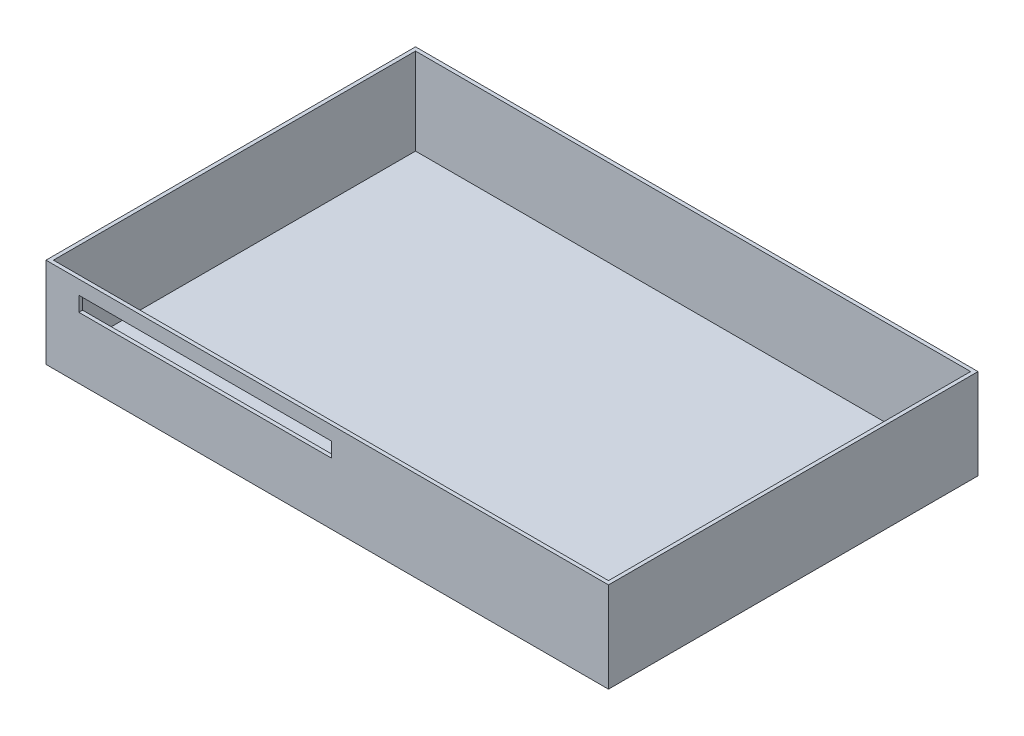
SolidWorks part; units mm, degrees
ref_plane "Front Plane" through (0, 0, 0) normal (0, 0, 1) x (1, 0, 0)
ref_plane "Top Plane" through (0, 0, 0) normal (0, 1, 0) x (1, 0, 0)
ref_plane "Right Plane" through (0, 0, 0) normal (1, 0, 0) x (0, 0, -1)
sketch "Sketch1" plane through (0, 0, 0) normal (0, 1, 0) x (1, 0, 0)
  line L1 (0, 0) -> (1370, 0)
  line L2 (0, 0) -> (0, 900)
  line L3 (0, 900) -> (1370, 900)
  line L4 (1370, 0) -> (1370, 900)
  dimension "D1" = 1370
  dimension "D2" = 900
extrude "Boss-Extrude1" add sketch "Sketch1" along normal blind 220
shell "Shell1" thickness 9
sketch "Sketch3" plane through (0, 0, 0) normal (0, 0, 1) x (1, 0, 0)
  line L1 (80, 186) -> (695, 186)
  line L2 (80, 186) -> (80, 150)
  line L3 (80, 150) -> (695, 150)
  line L4 (695, 186) -> (695, 150)
  dimension "D1" = 615
  dimension "D2" = 36
  dimension "D3" = 80
  dimension "D4" = 150
extrude "Cut-Extrude1" cut sketch "Sketch3" against normal up to next
